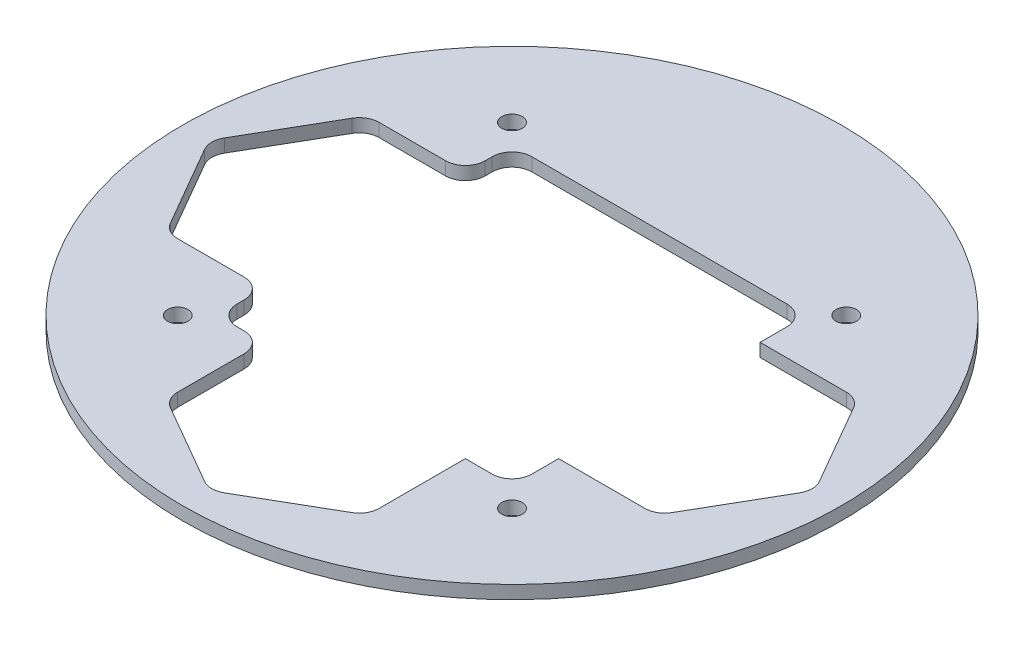
SolidWorks part; units mm, degrees
ref_plane "Front Plane" through (0, 0, 0) normal (0, 0, 1) x (1, 0, 0)
ref_plane "Top Plane" through (0, 0, 0) normal (0, 1, 0) x (1, 0, 0)
ref_plane "Right Plane" through (0, 0, 0) normal (1, 0, 0) x (0, 0, -1)
sketch "Sketch1" plane through (0, 0, 0) normal (0, 1, 0) x (1, 0, 0)
  line L0 (-25.3553, 25.3553) -> (25.3553, 25.3553) construction
  line L1 (-35.3553, -35.3553) -> (35.3553, -35.3553) construction
  line L2 (-35.3553, -35.3553) -> (-35.3553, 35.3553) construction
  line L3 (-35.3553, 35.3553) -> (35.3553, 35.3553) construction
  line L4 (35.3553, -35.3553) -> (35.3553, 35.3553) construction
  line L5 (-35.3553, -35.3553) -> (35.3553, 35.3553) construction
  line L6 (-35.3553, 35.3553) -> (35.3553, -35.3553) construction
  line L7 (25.3553, -25.3553) -> (25.3553, 25.3553) construction
  line L8 (-25.3553, -25.3553) -> (25.3553, -25.3553) construction
  line L9 (-25.3553, -25.3553) -> (-25.3553, 25.3553) construction
  line L10 (-28.3553, 28.3553) -> (28.3553, 28.3553)
  line L11 (28.3553, -28.3553) -> (28.3553, 28.3553)
  line L12 (-28.3553, -28.3553) -> (28.3553, -28.3553)
  line L13 (-28.3553, -28.3553) -> (-28.3553, 28.3553)
  line L14 (-22.3553, 22.3553) -> (22.3553, 22.3553)
  line L15 (22.3553, -22.3553) -> (22.3553, 22.3553)
  line L16 (-22.3553, -22.3553) -> (22.3553, -22.3553)
  line L17 (-22.3553, -22.3553) -> (-22.3553, 22.3553)
  line L18 (-28.3553, 0) -> (-50, 0) construction
  line L19 (0, -55) -> (0, 55) construction
  line L20 (-50, 0) -> (-50, 20.5281) construction
  line L21 (-46, 0) -> (-46, 20.5281) construction
  line L22 (0, 10.7107) -> (15.2807, 19.533)
  line L23 (-46, 0) -> (-37.1777, -15.2807)
  line L24 (-37.1777, -15.2807) -> (-19.533, -15.2807)
  line L25 (-19.533, -15.2807) -> (-10.7107, 0)
  line L26 (-10.7107, 0) -> (-19.533, 15.2807)
  line L27 (-19.533, 15.2807) -> (-37.1777, 15.2807)
  line L28 (-37.1777, 15.2807) -> (-46, 0)
  line L29 (15.2807, 19.533) -> (15.2807, 37.1777)
  line L30 (15.2807, 37.1777) -> (0, 46)
  line L31 (0, 46) -> (-15.2807, 37.1777)
  line L32 (-15.2807, 37.1777) -> (-15.2807, 19.533)
  line L33 (-15.2807, 19.533) -> (0, 10.7107)
  line L34 (10.7107, 0) -> (19.533, -15.2807)
  line L35 (19.533, -15.2807) -> (37.1777, -15.2807)
  line L36 (37.1777, -15.2807) -> (46, 0)
  line L37 (46, 0) -> (37.1777, 15.2807)
  line L38 (37.1777, 15.2807) -> (19.533, 15.2807)
  line L39 (19.533, 15.2807) -> (10.7107, 0)
  line L40 (0, -10.7107) -> (-15.2807, -19.533)
  line L41 (-15.2807, -19.533) -> (-15.2807, -37.1777)
  line L42 (-15.2807, -37.1777) -> (0, -46)
  line L43 (0, -46) -> (15.2807, -37.1777)
  line L44 (15.2807, -37.1777) -> (15.2807, -19.533)
  line L45 (15.2807, -19.533) -> (0, -10.7107)
  circle A0 centre (0, 0) radius 50
  circle A2 centre (-25.3553, 25.3553) radius 1.55
  circle A3 centre (25.3553, 25.3553) radius 1.55
  circle A4 centre (-25.3553, -25.3553) radius 1.55
  circle A5 centre (25.3553, -25.3553) radius 1.55
  circle A6 centre (-28.3553, 0) radius 15.2807 construction
  point P57 (0, 0)
  dimension "D1" = 10
  dimension "D4" = 100
  dimension "D2" = 3
  dimension "D3" = 3
  dimension "D5" = 4
  dimension "D6" = 4
extrude "Boss-Extrude2" add sketch "Sketch1" along normal blind 2 contours L31 L32 L10 L29 L30 | L10 L32 L14 L29 | L38 L11 L10 L29 L14 L15 A3 | L32 L10 L13 L27 L17 L14 A2 | L41 L16 L17 L24 L13 L12 A4 | L44 L12 L11 L35 L15 L16 A5 | A0 L44 L43 L42 L41 L12 L13 L24 L23 L28 L27 L10 L32 L31 L30 L29 L11 L38 L37 L36 L35
fillet "Fillet1" radius 3 16 edges at (-22.3553, 1, 22.3553) (0, 1, 46) (15.2807, 1, 37.1777) (22.3553, 1, 22.3553) (37.1777, 1, 15.2807) (46, 1, 0) (37.1777, 1, -15.2807) (22.3553, 1, -22.3553) (-15.2807, 1, 37.1777) (-15.2807, 1, 22.3553) (-22.3553, 1, 15.2807) (-37.1777, 1, 15.2807) (-46, 1, 0) (-22.3553, 1, -15.2807) (-37.1777, 1, -15.2807) (-22.3553, 1, -22.3553)
